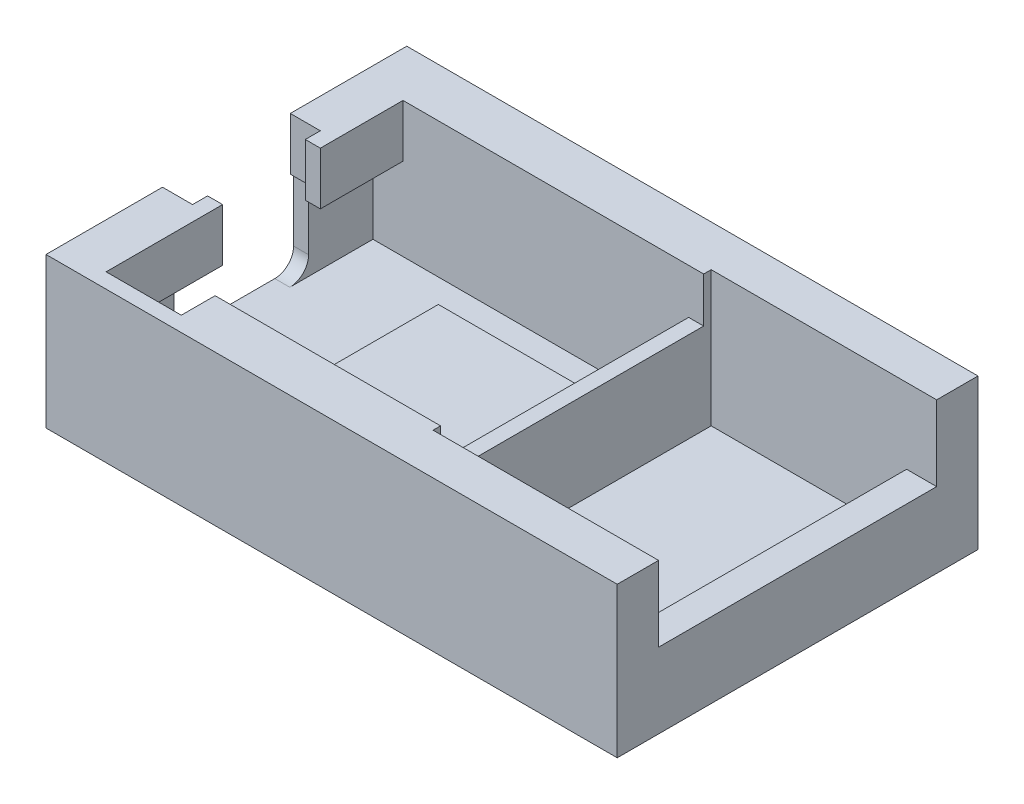
SolidWorks part; units mm, degrees
ref_plane "Front Plane" through (0, 0, 0) normal (0, 0, 1) x (1, 0, 0)
ref_plane "Top Plane" through (0, 0, 0) normal (0, 1, 0) x (1, 0, 0)
ref_plane "Right Plane" through (0, 0, 0) normal (1, 0, 0) x (0, 0, -1)
sketch "Sketch1" plane through (0, 0, 0) normal (0, 1, 0) x (1, 0, 0)
  line L1 (0, 0) -> (40, 0)
  line L2 (0, 0) -> (0, 24)
  line L3 (0, 24) -> (40, 24)
  line L4 (40, 0) -> (40, 24)
  dimension "D1" = 24
  dimension "D2" = 40
extrude "Boss-Extrude1" add sketch "Sketch1" along normal blind 1
sketch "Sketch2" plane through (0, 1, 0) normal (0, 1, 0) x (1, 0, 0)
  line L1 (0, 24) -> (40, 24)
  line L2 (0, 24) -> (0, 0)
  line L3 (0, 0) -> (40, 0)
  line L4 (40, 24) -> (40, 0)
  line L5 (1, 20.75) -> (22, 20.75)
  line L6 (1, 20.75) -> (1, 3.25)
  line L7 (1, 3.25) -> (22, 3.25)
  line L8 (22, 20.75) -> (22, 3.25)
  line L9 (23, 21.25) -> (36, 21.25)
  line L10 (23, 21.25) -> (23, 2.75)
  line L11 (23, 2.75) -> (36, 2.75)
  line L12 (36, 21.25) -> (36, 2.75)
  dimension "D1" = 17.5
  dimension "D2" = 21
  dimension "D3" = 3.25
  dimension "D4" = 1
  dimension "D5" = 18.5
  dimension "D6" = 13
  dimension "D7" = 1
  dimension "D8" = 2.75
extrude "Boss-Extrude3" add sketch "Sketch2" along normal blind 9
sketch "Sketch3" plane through (0, 10, 0) normal (0, 1, 0) x (1, 0, 0)
  line L0 (22, 20.75) -> (23, 20.75)
  line L1 (23, 21.25) -> (23, 2.75) construction
  line L2 (22, 20.75) -> (22, 3.25)
  line L3 (22, 3.25) -> (23, 3.25)
  line L4 (23, 21.25) -> (23, 2.75) construction
  line L5 (23, 3.25) -> (23, 20.75)
extrude "Cut-Extrude2" cut sketch "Sketch3" against normal blind 3
sketch "Sketch4" plane through (0, 1, 0) normal (0, 1, 0) x (1, 0, 0)
  line L0 (22, 20.75) -> (22, 3.25) construction
  line L1 (8.14, 17.96) -> (18.38, 17.96)
  line L2 (8.14, 17.96) -> (8.14, 6.04)
  line L3 (8.14, 6.04) -> (18.38, 6.04)
  line L4 (18.38, 17.96) -> (18.38, 6.04)
  line L5 (22, 20.75) -> (1, 20.75) construction
  line L6 (1, 3.25) -> (22, 3.25) construction
  line L7 (1, 20.75) -> (1, 3.25) construction
  dimension "D1" = 3.62
  dimension "D2" = 2.79
  dimension "D3" = 2.79
  dimension "D4" = 7.14
extrude "Boss-Extrude4" add sketch "Sketch4" along normal blind 1.21
sketch "Sketch5" plane through (1, 0, 0) normal (1, 0, 0) x (0, 0, -1)
  line L0 (7.53, 2.25) -> (7.53, 2.96)
  line L1 (8.78, 1) -> (15.22, 1)
  line L3 (16.47, 2.96) -> (16.47, 2.25)
  line L4 (20.75, 1) -> (3.25, 1) construction
  line L5 (3.25, 10) -> (3.25, 1) construction
  line L6 (7.53, 2.96) -> (7.53, 10)
  line L7 (20.75, 10) -> (3.25, 10) construction
  line L8 (7.53, 10) -> (16.47, 10)
  line L9 (16.47, 10) -> (16.47, 2.96)
  line L10 (20.75, 10) -> (20.75, 1) construction
  arc A0 (7.53, 2.25) -> (8.78, 1) centre (8.78, 2.25) ccw
  arc A3 (15.22, 1) -> (16.47, 2.25) centre (15.22, 2.25) ccw
  dimension "D7" = 1.25
  dimension "D1" = 1.25
  dimension "D2" = 0.71
  dimension "D3" = 6.44
  dimension "D4" = 4.28
  dimension "D9" = 0.71
  dimension "D10" = 4.28
extrude "Cut-Extrude3" cut sketch "Sketch5" against normal blind 2
sketch "Sketch8" plane through (0, 10, 0) normal (0, 1, 0) x (1, 0, 0)
  line L0 (36, 21.25) -> (40, 21.25)
  line L1 (40, 0) -> (40, 24) construction
  line L2 (36, 2.75) -> (40, 2.75)
  line L3 (40, 2.75) -> (40, 21.25)
  line L4 (36, 21.25) -> (36, 2.75)
extrude "Cut-Extrude4" cut sketch "Sketch8" against normal blind 5
sketch "Sketch10" plane through (0, 10, 0) normal (0, 1, 0) x (1, 0, 0)
sketch "Sketch11" plane through (40, 0, 0) normal (1, 0, 0) x (0, 0, -1)
  line L0 (21.25, 10) -> (24, 10) construction
  line L1 (0, 0) -> (24, 0)
  line L2 (0, 0) -> (0, 10)
  line L3 (0, 10) -> (24, 10)
  line L4 (24, 0) -> (24, 10)
  line L5 (24, 10) -> (24, 0) construction
extrude "Cut-Extrude5" cut sketch "Sketch11" against normal blind 2
sketch "Sketch12" plane through (0, 10, 0) normal (0, 1, 0) x (1, 0, 0)
  line L0 (0, 24) -> (0, 16.47) construction
  line L1 (4, 1) -> (8, 1)
  line L2 (4, 1) -> (4, 4)
  line L3 (4, 4) -> (8, 4)
  line L4 (8, 1) -> (8, 4)
  line L5 (0, 0) -> (38, 0) construction
  dimension "D1" = 4
  dimension "D2" = 1
  dimension "D3" = 3
  dimension "D4" = 4
extrude "Cut-Extrude6" cut sketch "Sketch12" against normal blind 3
sketch "Sketch13" plane through (0, 10, 0) normal (0, 1, 0) x (1, 0, 0)
  line L0 (23, 20.75) -> (1, 20.75) construction
  line L2 (1, 16.47) -> (1, 20.75)
  line L3 (1, 20.75) -> (3, 20.75)
  line L5 (3, 20.75) -> (3, 15.25)
  line L8 (1, 3.25) -> (3, 3.25)
  line L10 (1, 3.25) -> (4, 3.25) construction
  line L14 (2, 7.75) -> (0, 7.75)
  line L16 (0, 16.47) -> (1, 16.47)
  line L17 (0, 16.47) -> (0, 16.25)
  line L18 (0, 16.25) -> (2, 16.25)
  line L21 (0, 7.75) -> (0, 7.53)
  line L22 (1, 7.53) -> (1, 3.25)
  line L23 (0, 7.53) -> (1, 7.53)
  line L26 (3, 15.25) -> (2, 15.25)
  line L27 (2, 16.25) -> (2, 15.25)
  line L30 (3, 8.75) -> (2, 8.75)
  line L31 (2, 7.75) -> (2, 8.75)
  line L32 (3, 8.75) -> (3, 3.25)
  dimension "D1" = 0.22
  dimension "D2" = 0.22
  dimension "D3" = 2
  dimension "D4" = 2
  dimension "D5" = 1
  dimension "D6" = 1
  dimension "D7" = 1
  dimension "D8" = 1
extrude "Boss-Extrude5" add sketch "Sketch13" against normal blind 3.5
sketch "Sketch14" plane through (0, 10, 0) normal (0, 1, 0) x (1, 0, 0)
  line L1 (4, 1) -> (3, 1)
  line L2 (4, 1) -> (4, 3.25)
  line L3 (4, 3.25) -> (3, 3.25)
  line L4 (3, 1) -> (3, 3.25)
extrude "Cut-Extrude7" cut sketch "Sketch14" against normal blind 3
